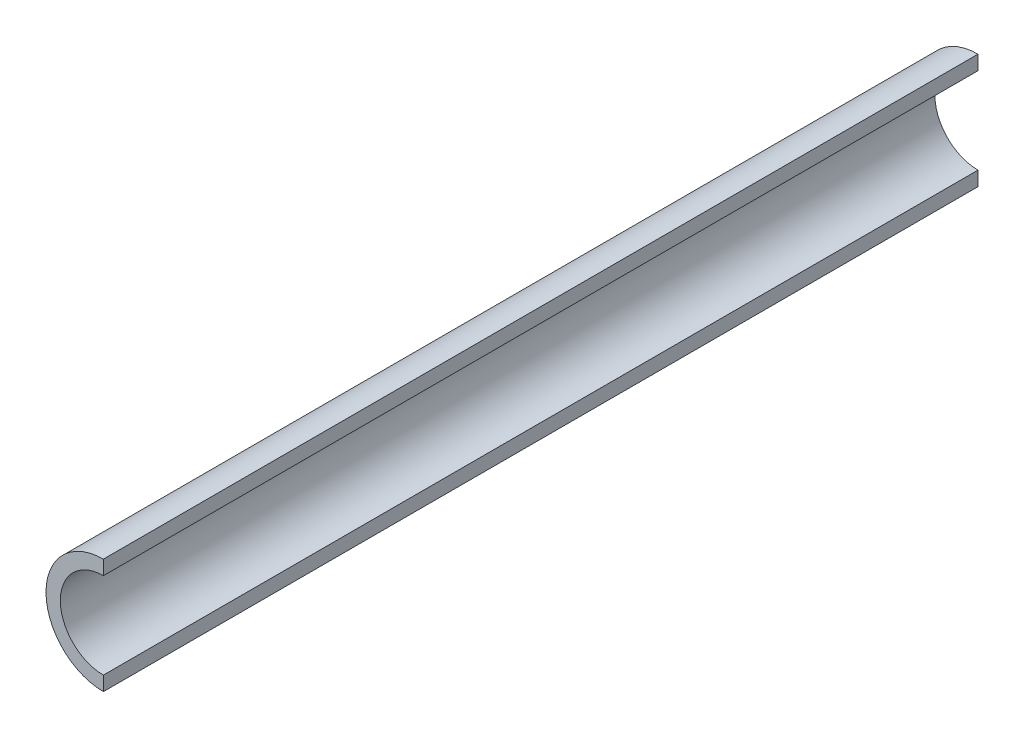
SolidWorks part; units mm, degrees
ref_plane "Front Plane" through (0, 0, 0) normal (1, 0, 0) x (0, 1, 0)
ref_plane "Top Plane" through (0, 0, 0) normal (0, 0, 1) x (0, 1, 0)
ref_plane "Right Plane" through (0, 0, 0) normal (0, 1, 0) x (-1, 0, 0)
sketch "Sketch3" plane through (0, 0, 0) normal (0, 0, 1) x (0, 1, 0)
  line L0 (0, 0) -> (5, 0)
  line L1 (40, 0) -> (35, 0)
  arc A0 (0, 0) -> (40, 0) centre (20, 0) cw
  arc A1 (5, 0) -> (35, 0) centre (20, 0) cw
  dimension "D1" = 20
  dimension "D2" = 5
  dimension "D3" = 5
extrude "Boss-Extrude3" add sketch "Sketch3" along normal blind 304.8 contours A0 L1 A1 L0
